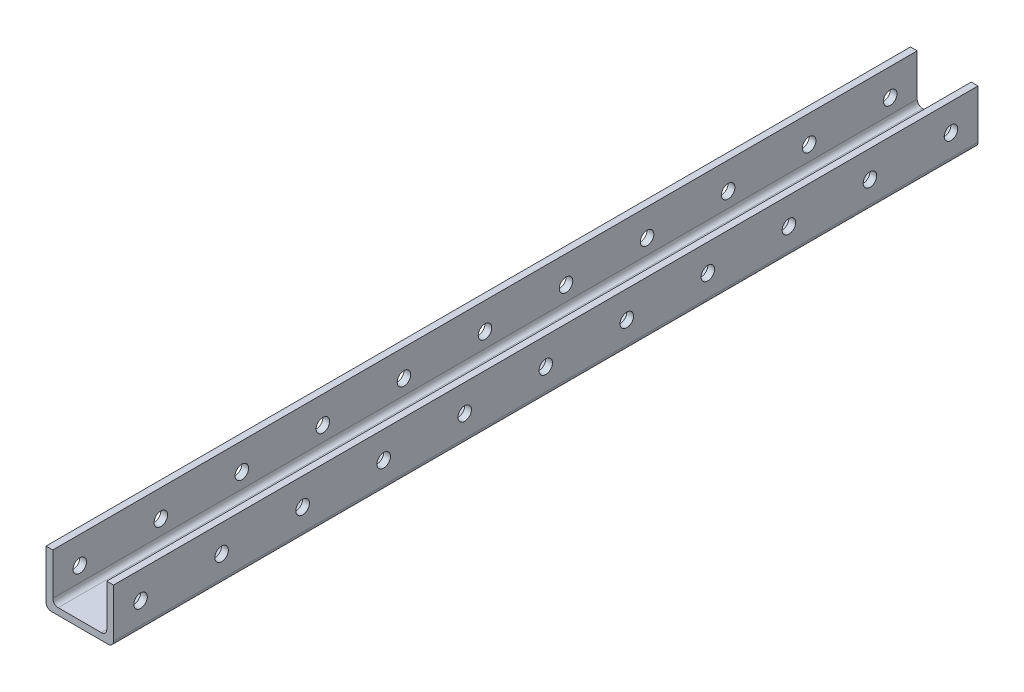
SolidWorks part; units mm, degrees
ref_plane "Front Plane" through (0, 0, 0) normal (0, 0, 1) x (1, 0, 0)
ref_plane "Top Plane" through (0, 0, 0) normal (0, 1, 0) x (1, 0, 0)
ref_plane "Right Plane" through (0, 0, 0) normal (1, 0, 0) x (0, 0, -1)
sketch "Sketch2" plane through (0, 0, 0) normal (0, 1, 0) x (1, 0, 0)
  line L1 (-15.875, -203.2) -> (15.875, -203.2)
  line L2 (-15.875, -203.2) -> (-15.875, 203.2)
  line L3 (-15.875, 203.2) -> (15.875, 203.2)
  line L4 (15.875, -203.2) -> (15.875, 203.2)
  line L5 (-15.875, -203.2) -> (15.875, 203.2) construction
  line L6 (-15.875, 203.2) -> (15.875, -203.2) construction
  point P0 (0, 0)
  dimension "D1" = 31.75
  dimension "D2" = 406.4
extrude "Boss-Extrude1" add sketch "Sketch2" along normal blind 25.4
sketch "Sketch3" plane through (0, 0, 203.2) normal (0, 0, 1) x (1, 0, 0)
  line L0 (-15.875, 25.4) -> (15.875, 25.4) construction
  line L1 (-12.7, 25.4) -> (12.7, 25.4)
  line L2 (-12.7, 25.4) -> (-12.7, 3.175)
  line L3 (-12.7, 3.175) -> (12.7, 3.175)
  line L4 (12.7, 25.4) -> (12.7, 3.175)
  line L5 (-15.875, 25.4) -> (-15.875, 0) construction
  line L6 (15.875, 25.4) -> (15.875, 0) construction
  line L7 (-15.875, 0) -> (15.875, 0) construction
  dimension "D1" = 3.175
  dimension "D2" = 3.175
  dimension "D3" = 3.175
extrude "Cut-Extrude1" cut sketch "Sketch3" against normal blind 406.4
fillet "Fillet1" radius 2.54 2 edges at (-15.875, 0, 0) (15.875, 0, 0)
fillet "Fillet3" radius 2.54 2 edges at (12.7, 3.175, 0) (-12.7, 3.175, 0)
sketch "Sketch4" plane through (15.875, 0, 0) normal (1, 0, 0) x (0, 0, -1)
  line L0 (203.2, 0) -> (-203.2, 0) construction
  line L1 (-203.2, 25.4) -> (-203.2, 2.54) construction
  line L2 (203.2, 25.4) -> (203.2, 2.54) construction
  circle A0 centre (-190.5, 12.7) radius 3.175
  circle A1 centre (-152.4, 12.7) radius 3.175
  circle A2 centre (-114.3, 12.7) radius 3.175
  circle A3 centre (-76.2, 12.7) radius 3.175
  circle A4 centre (-38.1, 12.7) radius 3.175
  circle A5 centre (0, 12.7) radius 3.175
  circle A6 centre (38.1, 12.7) radius 3.175
  circle A7 centre (76.2, 12.7) radius 3.175
  circle A8 centre (114.3, 12.7) radius 3.175
  circle A9 centre (152.4, 12.7) radius 3.175
  circle A10 centre (190.5, 12.7) radius 3.175
  dimension "D1" = 6.35
  dimension "D2" = 12.7
  dimension "D3" = 12.7
  dimension "D5" = 12.7
  dimension "D4" = 11
extrude "Cut-Extrude2" cut sketch "Sketch4" against normal blind 50.8
